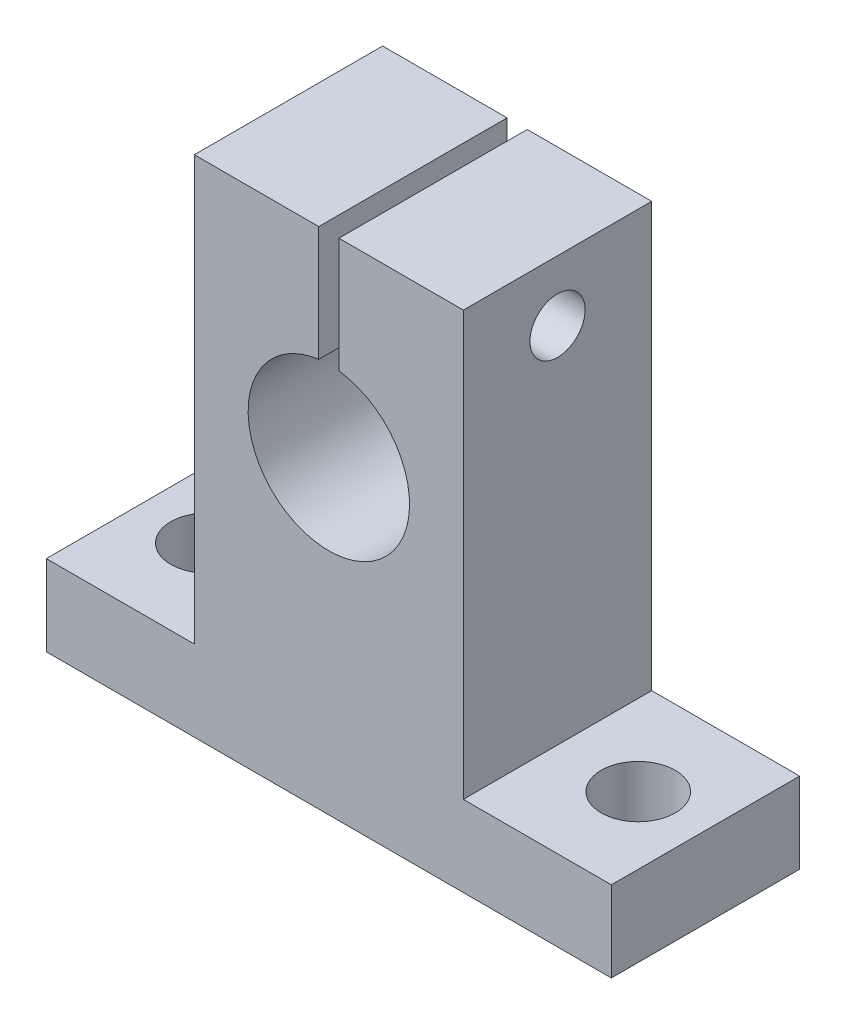
SolidWorks part; units mm, degrees
ref_plane "Front Plane" through (0, 0, 0) normal (0, 0, 1) x (1, 0, 0)
ref_plane "Top Plane" through (0, 0, 0) normal (0, 1, 0) x (1, 0, 0)
ref_plane "Right Plane" through (0, 0, 0) normal (1, 0, 0) x (0, 0, -1)
sketch "Sketch1" plane through (0, 0, 0) normal (0, 0, 1) x (1, 0, 0)
  line L0 (0, 0) -> (21, 0)
  line L1 (21, 0) -> (21, 6)
  line L2 (21, 6) -> (10, 6)
  line L3 (10, 6) -> (10, 37.5)
  line L4 (10, 37.5) -> (0, 37.5)
  line L5 (0, 37.5) -> (0, 0)
  line L9 (0, -1000) -> (0, 49000) construction
  dimension "D1" = 37.5
  dimension "D2" = 6
  dimension "D3" = 21
  dimension "D4" = 10
extrude "Boss-Extrude1" add sketch "Sketch1" along normal mid plane 14
mirror "Mirror1" about plane through (0, 37.5, 7) normal (1, 0, 0) of "Boss-Extrude1"
sketch "Sketch2" plane through (0, 0, 7) normal (0, 0, 1) x (1, 0, 0)
  circle A0 centre (0, 23) radius 6
  dimension "D1" = 12
  dimension "D2" = 23
extrude "Cut-Extrude1" cut sketch "Sketch2" against normal through all
sketch "Sketch3" plane through (10, 0, 0) normal (1, 0, 0) x (0, 0, -1)
  line L1 (-7, 37.5) -> (7, 37.5) construction
  circle A0 centre (0, 33) radius 2.05
  dimension "D2" = 4.1
  dimension "D1" = 4.5
extrude "Cut-Extrude2" cut sketch "Sketch3" against normal through all
sketch "Sketch4" plane through (0, 6, 0) normal (0, 1, 0) x (1, 0, 0)
  circle A0 centre (-16, 0) radius 2.75
  circle A1 centre (16, 0) radius 2.75
  dimension "D2" = 5.5
  dimension "D3" = 5.5
  dimension "D1" = 16
  dimension "D4" = 16
extrude "Cut-Extrude3" cut sketch "Sketch4" against normal blind 14
sketch "Sketch5" plane through (0, 0, 7) normal (0, 0, 1) x (1, 0, 0)
  line L0 (-0.75, 52) -> (-0.75, 23)
  line L1 (-0.75, 52) -> (0.75, 52)
  line L2 (-0.75, 23) -> (0.75, 23)
  line L3 (0.75, 52) -> (0.75, 23)
  line L4 (-0.75, 52) -> (0.75, 23) construction
  line L5 (-0.75, 23) -> (0.75, 52) construction
  line L7 (10, 37.5) -> (-10, 37.5) construction
  point P1 (0, 37.5)
  dimension "D1" = 1.5
  dimension "D2" = 90
extrude "Cut-Extrude4" cut sketch "Sketch5" against normal through all
